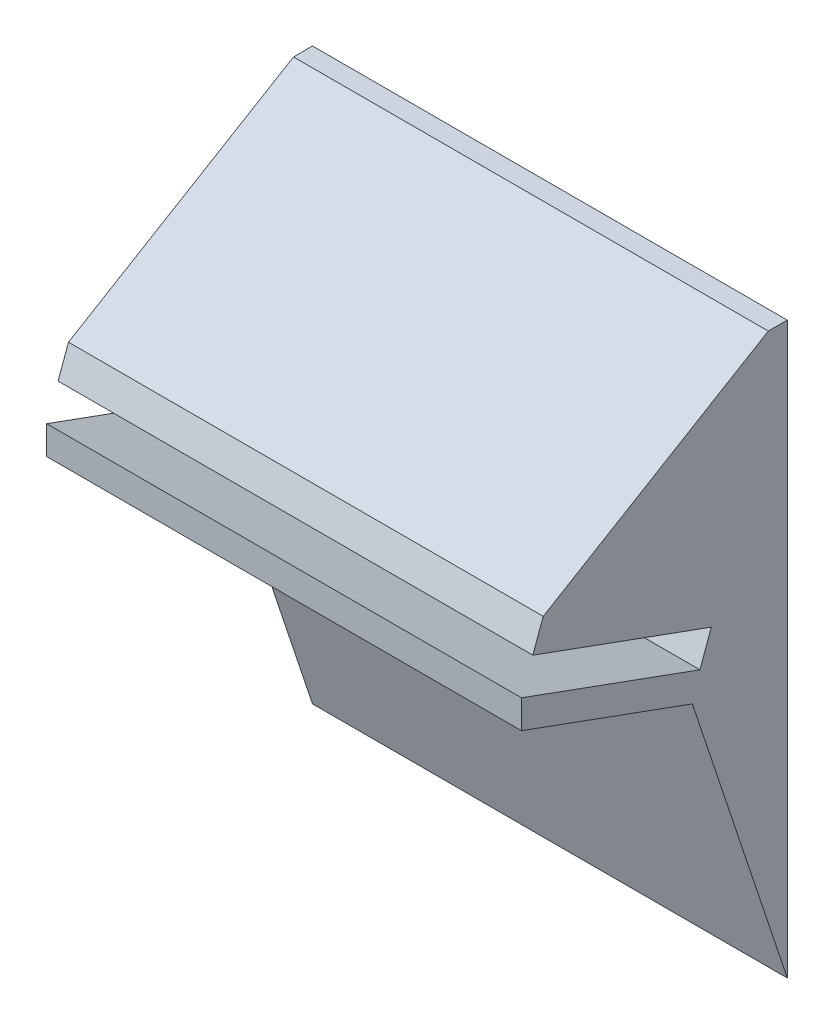
SolidWorks part; units mm, degrees
ref_plane "Plan de face" through (0, 0, 0) normal (0, 0, 1) x (1, 0, 0)
ref_plane "Plan de dessus" through (0, 0, 0) normal (0, 1, 0) x (1, 0, 0)
ref_plane "Plan de droite" through (0, 0, 0) normal (1, 0, 0) x (0, 0, -1)
sketch "Esquisse1" plane through (0, 0, 0) normal (0, 0, 1) x (1, 0, 0)
  line L1 (0, 0) -> (50, 0)
  line L2 (0, 0) -> (0, 30)
  line L3 (0, 30) -> (50, 30)
  line L4 (50, 0) -> (50, 30)
  dimension "D1" = 50
  dimension "D2" = 30
extrude "Boss.-Extru.1" add sketch "Esquisse1" along normal blind 2
sketch "Esquisse2" plane through (50, 0, 0) normal (1, 0, 0) x (0, 0, -1)
  line L0 (-2, 0) -> (-10, 0)
  line L1 (-10, 0) -> (-27.9909, 6.5482)
  line L2 (-27.9909, 6.5482) -> (-27.9909, 9.5482)
  line L3 (-27.9909, 9.5482) -> (-9.1971, 2.7078)
  line L4 (-9.1971, 2.7078) -> (-8, 5.9967)
  line L5 (-8, 5.9967) -> (-26.7939, 12.8371)
  line L6 (-26.7939, 12.8371) -> (-25.7019, 15.8371)
  line L7 (-25.7019, 15.8371) -> (-2, 30)
  line L8 (-2, 30) -> (-2, 0)
  line L9 (0, 0) -> (0, 30) construction
  dimension "D1" = 20
  dimension "D2" = 3.5
  dimension "D3" = 70
  dimension "D4" = 8
  dimension "D5" = 3
  dimension "D6" = 20
  dimension "D7" = 8
  dimension "D8" = 0
  dimension "D9" = 3
extrude "Boss.-Extru.2" add sketch "Esquisse2" against normal up to surface (50 mm away) up to face at (0, 15, 1)
sketch "Esquisse4" plane through (50, 0, 0) normal (1, 0, 0) x (0, 0, -1)
  line L0 (0, 0) -> (0, -30)
  line L1 (0, -30) -> (-10, 0)
  line L2 (-10, 0) -> (0, 0)
  dimension "D1" = 30
extrude "Boss.-Extru.4" add sketch "Esquisse4" against normal up to surface (50 mm away) up to face at (0, 11.3475, 13.7675)
